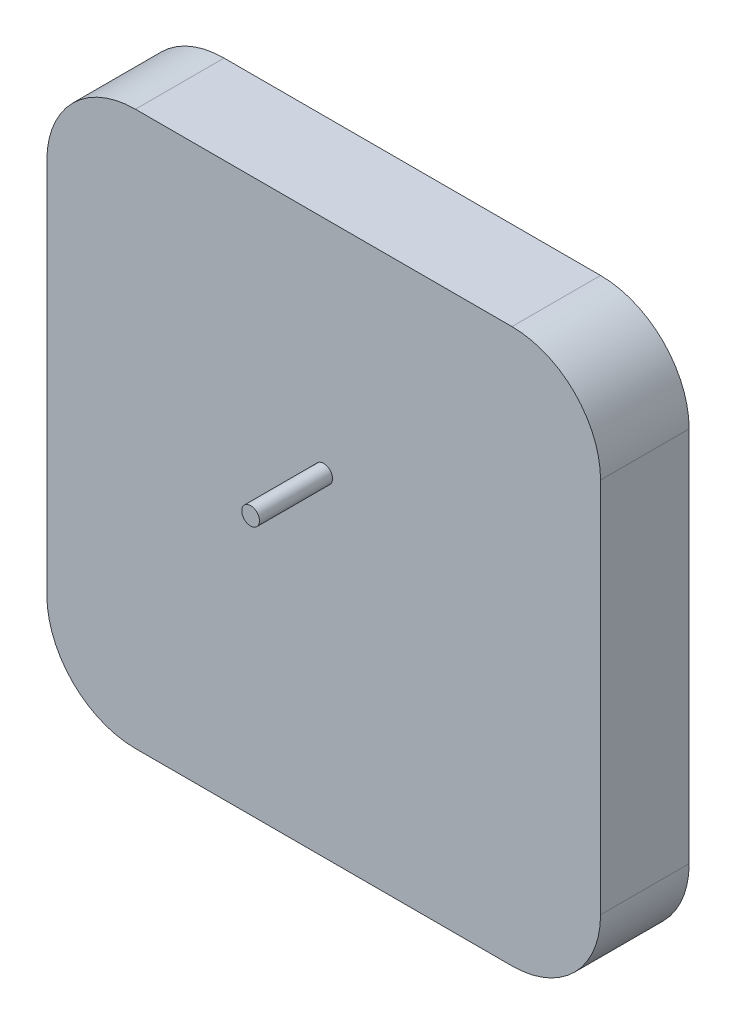
SolidWorks part; units mm, degrees
ref_plane "Спереди" through (0, 0, 0) normal (0, 0, 1) x (1, 0, 0)
ref_plane "Сверху" through (0, 0, 0) normal (0, 1, 0) x (1, 0, 0)
ref_plane "Справа" through (0, 0, 0) normal (1, 0, 0) x (0, 0, -1)
sketch "Эскиз1" plane through (0, 0, 0) normal (0, 0, 1) x (1, 0, 0)
  line L1 (-8.5, 12.5) -> (8.5, 12.5)
  line L2 (-12.5, 8.5) -> (-12.5, -8.5)
  line L3 (-8.5, -12.5) -> (8.5, -12.5)
  line L4 (12.5, 8.5) -> (12.5, -8.5)
  line L5 (-12.5, 12.5) -> (12.5, -12.5) construction
  line L6 (-12.5, -12.5) -> (12.5, 12.5) construction
  arc A0 (8.5, -12.5) -> (12.5, -8.5) centre (8.5, -8.5) ccw
  arc A1 (-12.5, -8.5) -> (-8.5, -12.5) centre (-8.5, -8.5) ccw
  arc A2 (-8.5, 12.5) -> (-12.5, 8.5) centre (-8.5, 8.5) ccw
  arc A3 (8.5, 12.5) -> (12.5, 8.5) centre (8.5, 8.5) cw
  point P0 (0, 0)
  dimension "D3" = 4
  dimension "D1" = 25
  dimension "D2" = 25
extrude "Бобышка-Вытянуть1" add sketch "Эскиз1" along normal blind 4
sketch "Эскиз2" plane through (0, 0, 4) normal (0, 0, 1) x (1, 0, 0)
  line L0 (0, -15.1403) -> (0, 16.3245) construction
  line L1 (-14.1676, 0) -> (14.7174, 0) construction
  circle A0 centre (0, 2.5) radius 0.4
  dimension "D1" = 0.8
  dimension "D2" = 2.5
extrude "Бобышка-Вытянуть2" add sketch "Эскиз2" along normal blind 3.3
sketch "Эскиз3" plane through (0, 0, 0) normal (0, 0, -1) x (-1, 0, 0)
  circle A0 centre (0, 2.5) radius 1.5
  dimension "D1" = 3
extrude "Бобышка-Вытянуть3" add sketch "Эскиз3" along normal blind 0.7
